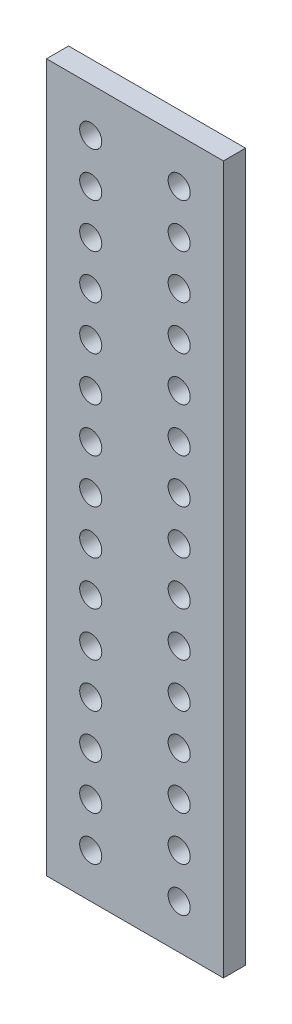
SolidWorks part; units mm, degrees
ref_plane "Front Plane" through (0, 0, 0) normal (0, 0, 1) x (1, 0, 0)
ref_plane "Top Plane" through (0, 0, 0) normal (0, 1, 0) x (1, 0, 0)
ref_plane "Right Plane" through (0, 0, 0) normal (1, 0, 0) x (0, 0, -1)
sketch "Sketch1" plane through (0, 0, 0) normal (0, 0, 1) x (1, 0, 0)
  line L1 (-25.4, -101.6) -> (25.4, -101.6)
  line L2 (-25.4, -101.6) -> (-25.4, 101.6)
  line L3 (-25.4, 101.6) -> (25.4, 101.6)
  line L4 (25.4, -101.6) -> (25.4, 101.6)
  line L5 (-25.4, -101.6) -> (25.4, 101.6) construction
  line L6 (-25.4, 101.6) -> (25.4, -101.6) construction
  circle A0 centre (-12.7, 88.9) radius 3.175
  circle A1 centre (12.7, 88.9) radius 3.175
  circle A2 centre (12.7, 76.2) radius 3.175
  circle A3 centre (12.7, 63.5) radius 3.175
  circle A4 centre (12.7, 50.8) radius 3.175
  circle A5 centre (12.7, 38.1) radius 3.175
  circle A6 centre (12.7, 25.4) radius 3.175
  circle A7 centre (12.7, 12.7) radius 3.175
  circle A8 centre (12.7, 0) radius 3.175
  circle A9 centre (12.7, -12.7) radius 3.175
  circle A10 centre (12.7, -25.4) radius 3.175
  circle A11 centre (12.7, -38.1) radius 3.175
  circle A12 centre (-12.7, -50.8) radius 3.175
  circle A13 centre (12.7, -50.8) radius 3.175
  circle A14 centre (-12.7, -63.5) radius 3.175
  circle A15 centre (12.7, -63.5) radius 3.175
  circle A16 centre (-12.7, -76.2) radius 3.175
  circle A17 centre (12.7, -76.2) radius 3.175
  circle A18 centre (-12.7, -88.9) radius 3.175
  circle A19 centre (12.7, -88.9) radius 3.175
  circle A24 centre (-12.7, 76.2) radius 3.175
  circle A25 centre (-12.7, 63.5) radius 3.175
  circle A26 centre (-12.7, 50.8) radius 3.175
  circle A27 centre (-12.7, 38.1) radius 3.175
  circle A28 centre (-12.7, 25.4) radius 3.175
  circle A29 centre (-12.7, 12.7) radius 3.175
  circle A30 centre (-12.7, 0) radius 3.175
  circle A31 centre (-12.7, -12.7) radius 3.175
  circle A32 centre (-12.7, -25.4) radius 3.175
  circle A33 centre (-12.7, -38.1) radius 3.175
  point P0 (0, 0)
  dimension "D3" = 6.35
  dimension "D1" = 50.8
  dimension "D2" = 203.2
  dimension "D4" = 12.7
  dimension "D5" = 12.7
  dimension "D6" = 2
  dimension "D7" = 15
extrude "Boss-Extrude1" add sketch "Sketch1" along normal blind 6.35
